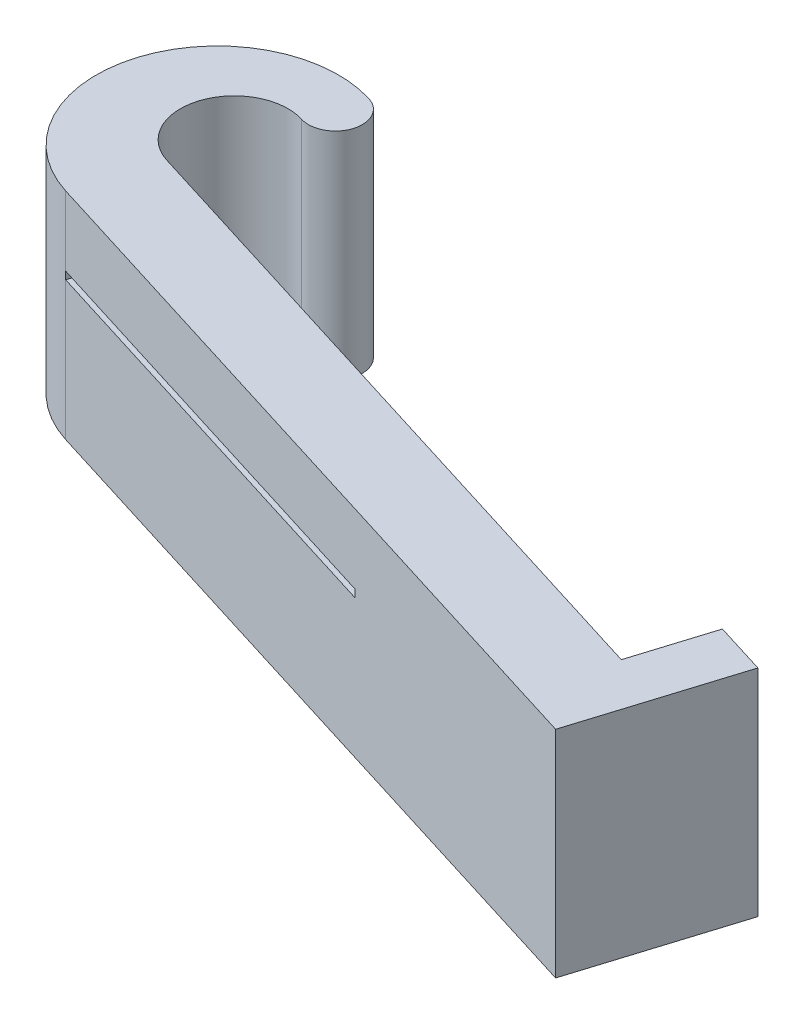
SolidWorks part; units mm, degrees
material "Custom Plastic"
ref_plane "X-Y Datum" through (0, 0, 0) normal (0, 0, 1) x (1, 0, 0)
ref_plane "X-Z Datum" through (0, 0, 0) normal (0, 1, 0) x (1, 0, 0)
ref_plane "Y-Z Datum" through (0, 0, 0) normal (1, 0, 0) x (0, 0, -1)
sketch "Sketch1" plane through (0, -33.4568, 0) normal (0, 1, 0) x (1, 0, 0)
  line L0 (-527.5066, -80.8426) -> (-695.2326, -28.6567)
  line L2 (-689.573, -10.4668) -> (-533.9736, -58.8796)
  line L3 (-533.9736, -58.8796) -> (-528.3141, -40.6898)
  line L4 (-528.3141, -40.6898) -> (-516.1875, -44.4628)
  line L5 (-516.1875, -44.4628) -> (-527.5066, -80.8426)
  line L6 (-695.2326, -28.6567) -> (-685.8, 1.6598) construction
  line L7 (-678.2539, 25.913) -> (-682.027, 13.7864) construction
  arc A1 (-678.2539, 25.913) -> (-682.027, 13.7864) centre (-680.1404, 19.8497) cw
  arc A3 (-689.573, -10.4668) -> (-682.027, 13.7864) centre (-685.8, 1.6598) cw
  arc A4 (-682.027, 13.7864) -> (-689.573, -10.4668) centre (-685.8, 1.6598) ccw construction
  arc A6 (-695.2326, -28.6567) -> (-678.2539, 25.913) centre (-686.7433, -1.3719) cw
  dimension "D1" = 12.7
extrude "Boss-Extrude1" add sketch "Sketch1" along normal up to surface (50.8 mm away)
sketch "Sketch2" plane through (0, 0, 0) normal (0, 1, 0) x (1, 0, 0)
  line L1 (-727.9349, 87.1721) -> (-507.9349, 87.1721)
  line L2 (-727.9349, 87.1721) -> (-727.9349, -132.8279)
  line L3 (-727.9349, -132.8279) -> (-507.9349, -132.8279)
  line L4 (-507.9349, 87.1721) -> (-507.9349, -132.8279)
  line L5 (-617.9349, -132.8279) -> (-617.9349, 87.1721) construction
  line L6 (-727.9349, -22.8279) -> (-507.9349, -22.8279) construction
  point P92 (-617.9349, -22.8279)
  dimension "D1" = 220
sketch "Sketch3" plane through (-69.492, 0, 223.3481) normal (-0.2971, 0, 0.9548) x (0.9548, 0, 0.2971)
  line L0 (-655.329, 0.0712) -> (-551.5354, 0.0712) construction
  line L1 (-655.329, 17.3432) -> (-655.329, -33.4568) construction
  line L2 (-655.329, 17.3432) -> (-479.672, 17.3432) construction
  line L4 (-655.329, 0.9618) -> (-551.5354, 0.9618)
  line L5 (-655.329, 0.9618) -> (-655.329, -0.8194)
  line L6 (-655.329, -0.8194) -> (-551.5354, -0.8194)
  line L7 (-551.5354, 0.9618) -> (-551.5354, -0.8194)
  line L8 (-603.4322, -0.8194) -> (-603.4322, 0.9618) construction
  line L9 (-655.329, 0.0712) -> (-551.5354, 0.0712) construction
  point P2 (0, 0)
  point P5 (-603.4322, 0.9618)
  point P76 (-603.4322, 0.0712)
  dimension "D1" = 17.272
extrude "Cut-Extrude1" cut sketch "Sketch3" against normal blind 2.54
